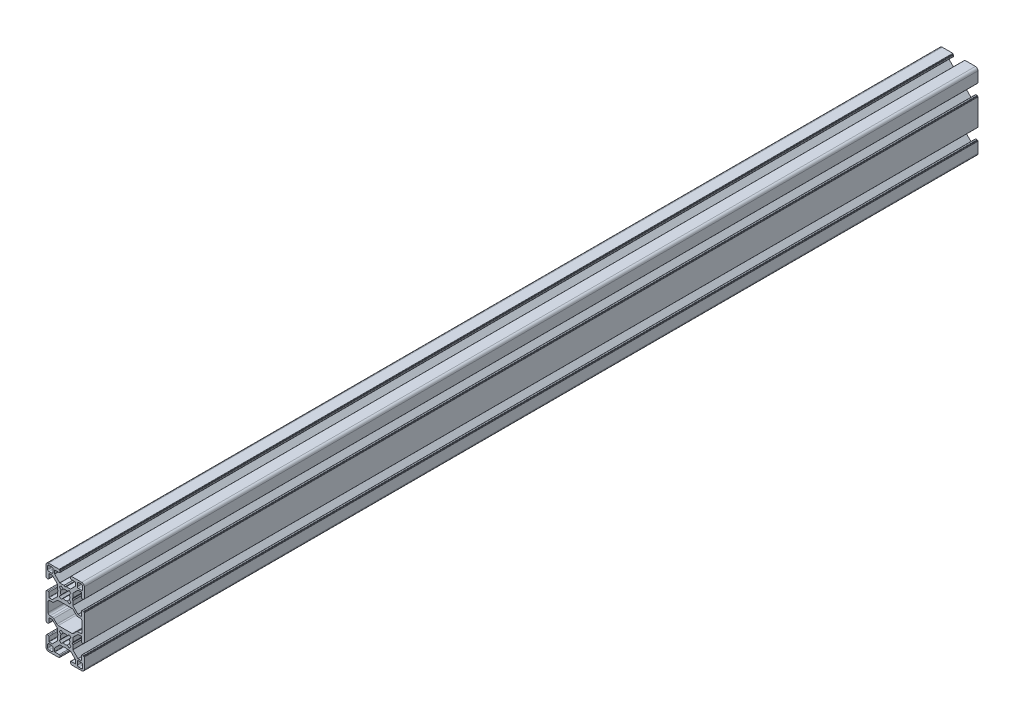
SolidWorks part; units mm, degrees
material "1060 Alloy"
ref_plane "Front" through (0, 0, 0) normal (0, 0, 1) x (1, 0, 0)
ref_plane "Top" through (0, 0, 0) normal (0, 1, 0) x (1, 0, 0)
ref_plane "Right" through (0, 0, 0) normal (1, 0, 0) x (0, 0, -1)
ref_plane "Plane1" through (0, 0, 25) normal (0, 0, 1) x (1, 0, 0)
sketch "Sketch1" plane through (0, 0, 25) normal (0, 0, 1) x (1, 0, 0)
  line L0 (-9.5, 12.7) -> (-9.5, 10.5)
  line L1 (-10.5, 9.5) -> (-12.7, 9.5)
  line L2 (-13.7, 10.5) -> (-13.7, 12.7)
  line L3 (-12.7, 13.7) -> (-10.5, 13.7)
  line L4 (12.7, 9.5) -> (10.5, 9.5)
  line L5 (9.5, 10.5) -> (9.5, 12.7)
  line L6 (10.5, 13.7) -> (12.7, 13.7)
  line L7 (13.7, 12.7) -> (13.7, 10.5)
  line L8 (-12.7, -39.5) -> (-10.5, -39.5)
  line L9 (-9.5, -40.5) -> (-9.5, -42.7)
  line L10 (-10.5, -43.7) -> (-12.7, -43.7)
  line L11 (-13.7, -42.7) -> (-13.7, -40.5)
  line L12 (9.5, -42.7) -> (9.5, -40.5)
  line L13 (10.5, -39.5) -> (12.7, -39.5)
  line L14 (13.7, -40.5) -> (13.7, -42.7)
  line L15 (12.7, -43.7) -> (10.5, -43.7)
  line L16 (-3.2806, 1.6001) -> (-4.5184, 3.1359)
  line L17 (-3.1547, 4.5053) -> (-1.6001, 3.2806)
  line L18 (1.6001, 3.2806) -> (3.1547, 4.5053)
  line L19 (4.5184, 3.1359) -> (3.2806, 1.6001)
  line L20 (3.2806, -1.6001) -> (4.5184, -3.1359)
  line L21 (3.1547, -4.5053) -> (1.6001, -3.2806)
  line L22 (-1.6001, -3.2806) -> (-3.1547, -4.5053)
  line L23 (-4.5184, -3.1359) -> (-3.2806, -1.6001)
  line L24 (-4.5184, -33.1359) -> (-3.2806, -31.6001)
  line L25 (-3.2806, -28.3999) -> (-4.5184, -26.8641)
  line L26 (-3.1547, -25.4947) -> (-1.6001, -26.7194)
  line L27 (1.6001, -26.7194) -> (3.1547, -25.4947)
  line L28 (4.5184, -26.8641) -> (3.2806, -28.3999)
  line L29 (3.2806, -31.6001) -> (4.5184, -33.1359)
  line L30 (3.1547, -34.5053) -> (1.6001, -33.2806)
  line L31 (-1.6001, -33.2806) -> (-3.1547, -34.5053)
  line L32 (8.9272, -20.5393) -> (6.4104, -23.0562)
  line L33 (5.3497, -23.4955) -> (-5.3497, -23.4955)
  line L34 (-6.4104, -23.0562) -> (-8.9272, -20.5393)
  line L35 (-9.9879, -20.1) -> (-11.85, -20.1)
  line L36 (-13.35, -18.6) -> (-13.35, -11.4)
  line L37 (-11.85, -9.9) -> (-9.9879, -9.9)
  line L38 (-8.9272, -9.4607) -> (-6.4104, -6.9438)
  line L39 (-5.3497, -6.5045) -> (5.3497, -6.5045)
  line L40 (6.4104, -6.9438) -> (8.9272, -9.4607)
  line L41 (9.9879, -9.9) -> (11.85, -9.9)
  line L42 (13.35, -11.4) -> (13.35, -18.6)
  line L43 (11.85, -20.1) -> (9.9879, -20.1)
  line L44 (13.4, -25.95) -> (14.3, -25.95)
  line L45 (14.5, -25.75) -> (14.5, -25.65)
  line L46 (14.7, -25.45) -> (14.8, -25.45)
  line L47 (15, -25.25) -> (15, -4.75)
  line L48 (14.8, -4.55) -> (14.7, -4.55)
  line L49 (14.5, -4.35) -> (14.5, -4.25)
  line L50 (14.3, -4.05) -> (13.4, -4.05)
  line L51 (12.8, -4.65) -> (12.8, -8.05)
  line L52 (12.6, -8.25) -> (10.1328, -8.25)
  line L53 (9.9914, -8.1914) -> (6.063, -4.263)
  line L54 (6.0045, -4.1216) -> (6.0045, -0.9)
  line L55 (6.0045, -0.9) -> (5.5426, -0.1)
  line L56 (5.5426, 0.1) -> (6.0045, 0.9)
  line L57 (6.0045, 0.9) -> (6.0045, 4.1216)
  line L58 (6.063, 4.263) -> (9.9914, 8.1914)
  line L59 (10.1328, 8.25) -> (12.6, 8.25)
  line L60 (12.8, 8.05) -> (12.8, 4.65)
  line L61 (13.4, 4.05) -> (14.3, 4.05)
  line L62 (14.5, 4.25) -> (14.5, 4.35)
  line L63 (14.7, 4.55) -> (14.8, 4.55)
  line L64 (15, 4.75) -> (15, 13)
  line L65 (13, 15) -> (4.75, 15)
  line L66 (4.55, 14.8) -> (4.55, 14.7)
  line L67 (4.35, 14.5) -> (4.25, 14.5)
  line L68 (4.05, 14.3) -> (4.05, 13.4)
  line L69 (4.65, 12.8) -> (8.05, 12.8)
  line L70 (8.25, 12.6) -> (8.25, 10.1328)
  line L71 (8.1914, 9.9914) -> (4.2586, 6.0586)
  line L72 (4.1172, 6) -> (0.9, 6)
  line L73 (0.9, 6) -> (0.1019, 5.5392)
  line L74 (-0.1019, 5.5392) -> (-0.9, 6)
  line L75 (-0.9, 6) -> (-4.1172, 6)
  line L76 (-4.2586, 6.0586) -> (-8.1914, 9.9914)
  line L77 (-8.25, 10.1328) -> (-8.25, 12.6)
  line L78 (-8.05, 12.8) -> (-4.65, 12.8)
  line L79 (-4.05, 13.4) -> (-4.05, 14.3)
  line L80 (-4.25, 14.5) -> (-4.35, 14.5)
  line L81 (-4.55, 14.7) -> (-4.55, 14.8)
  line L82 (-4.75, 15) -> (-13, 15)
  line L83 (-15, 13) -> (-15, 4.75)
  line L84 (-14.8, 4.55) -> (-14.7, 4.55)
  line L85 (-14.5, 4.35) -> (-14.5, 4.25)
  line L86 (-14.3, 4.05) -> (-13.4, 4.05)
  line L87 (-12.8, 4.65) -> (-12.8, 8.05)
  line L88 (-12.6, 8.25) -> (-10.1328, 8.25)
  line L89 (-9.9914, 8.1914) -> (-6.063, 4.263)
  line L90 (-6.0045, 4.1216) -> (-6.0045, 0.9)
  line L91 (-6.0045, 0.9) -> (-5.5426, 0.1)
  line L92 (-5.5426, -0.1) -> (-6.0045, -0.9)
  line L93 (-6.0045, -0.9) -> (-6.0045, -4.1216)
  line L94 (-6.063, -4.263) -> (-9.9914, -8.1914)
  line L95 (-10.1328, -8.25) -> (-12.6, -8.25)
  line L96 (-12.8, -8.05) -> (-12.8, -4.65)
  line L97 (-13.4, -4.05) -> (-14.3, -4.05)
  line L98 (-14.5, -4.25) -> (-14.5, -4.35)
  line L99 (-14.7, -4.55) -> (-14.8, -4.55)
  line L100 (-15, -4.75) -> (-15, -25.25)
  line L101 (-14.8, -25.45) -> (-14.7, -25.45)
  line L102 (-14.5, -25.65) -> (-14.5, -25.75)
  line L103 (-14.3, -25.95) -> (-13.4, -25.95)
  line L104 (-12.8, -25.35) -> (-12.8, -21.95)
  line L105 (-12.6, -21.75) -> (-10.1328, -21.75)
  line L106 (-9.9914, -21.8086) -> (-6.063, -25.737)
  line L107 (-6.0045, -25.8784) -> (-6.0045, -29.1)
  line L108 (-6.0045, -29.1) -> (-5.5426, -29.9)
  line L109 (-5.5426, -30.1) -> (-6.0045, -30.9)
  line L110 (-6.0045, -30.9) -> (-6.0045, -34.1216)
  line L111 (-6.063, -34.263) -> (-9.9914, -38.1914)
  line L112 (-10.1328, -38.25) -> (-12.6, -38.25)
  line L113 (-12.8, -38.05) -> (-12.8, -34.65)
  line L114 (-13.4, -34.05) -> (-14.3, -34.05)
  line L115 (-14.5, -34.25) -> (-14.5, -34.35)
  line L116 (-14.7, -34.55) -> (-14.8, -34.55)
  line L117 (-15, -34.75) -> (-15, -43)
  line L118 (-13, -45) -> (-4.75, -45)
  line L119 (-4.55, -44.8) -> (-4.55, -44.7)
  line L120 (-4.35, -44.5) -> (-4.25, -44.5)
  line L121 (-4.05, -44.3) -> (-4.05, -43.4)
  line L122 (-4.65, -42.8) -> (-8.05, -42.8)
  line L123 (-8.25, -42.6) -> (-8.25, -40.1328)
  line L124 (-8.1914, -39.9914) -> (-4.2586, -36.0586)
  line L125 (-4.1172, -36) -> (-0.9, -36)
  line L126 (-0.9, -36) -> (-0.1019, -35.5392)
  line L127 (0.1019, -35.5392) -> (0.9, -36)
  line L128 (0.9, -36) -> (4.1172, -36)
  line L129 (4.2586, -36.0586) -> (8.1914, -39.9914)
  line L130 (8.25, -40.1328) -> (8.25, -42.6)
  line L131 (8.05, -42.8) -> (4.65, -42.8)
  line L132 (4.05, -43.4) -> (4.05, -44.3)
  line L133 (4.25, -44.5) -> (4.35, -44.5)
  line L134 (4.55, -44.7) -> (4.55, -44.8)
  line L135 (4.75, -45) -> (13, -45)
  line L136 (15, -43) -> (15, -34.75)
  line L137 (14.8, -34.55) -> (14.7, -34.55)
  line L138 (14.5, -34.35) -> (14.5, -34.25)
  line L139 (14.3, -34.05) -> (13.4, -34.05)
  line L140 (12.8, -34.65) -> (12.8, -38.05)
  line L141 (12.6, -38.25) -> (10.1328, -38.25)
  line L142 (9.9914, -38.1914) -> (6.063, -34.263)
  line L143 (6.0045, -34.1216) -> (6.0045, -30.9)
  line L144 (6.0045, -30.9) -> (5.5426, -30.1)
  line L145 (5.5426, -29.9) -> (6.0045, -29.1)
  line L146 (6.0045, -29.1) -> (6.0045, -25.8784)
  line L147 (6.063, -25.737) -> (9.9914, -21.8086)
  line L148 (10.1328, -21.75) -> (12.6, -21.75)
  line L149 (12.8, -21.95) -> (12.8, -25.35)
  arc A0 (-9.5, 10.5) -> (-10.5, 9.5) centre (-10.5, 10.5) cw
  arc A1 (-12.7, 9.5) -> (-13.7, 10.5) centre (-12.7, 10.5) cw
  arc A2 (-13.7, 12.7) -> (-12.7, 13.7) centre (-12.7, 12.7) cw
  arc A3 (-10.5, 13.7) -> (-9.5, 12.7) centre (-10.5, 12.7) cw
  arc A4 (10.5, 9.5) -> (9.5, 10.5) centre (10.5, 10.5) cw
  arc A5 (9.5, 12.7) -> (10.5, 13.7) centre (10.5, 12.7) cw
  arc A6 (12.7, 13.7) -> (13.7, 12.7) centre (12.7, 12.7) cw
  arc A7 (13.7, 10.5) -> (12.7, 9.5) centre (12.7, 10.5) cw
  arc A8 (-10.5, -39.5) -> (-9.5, -40.5) centre (-10.5, -40.5) cw
  arc A9 (-9.5, -42.7) -> (-10.5, -43.7) centre (-10.5, -42.7) cw
  arc A10 (-12.7, -43.7) -> (-13.7, -42.7) centre (-12.7, -42.7) cw
  arc A11 (-13.7, -40.5) -> (-12.7, -39.5) centre (-12.7, -40.5) cw
  arc A12 (9.5, -40.5) -> (10.5, -39.5) centre (10.5, -40.5) cw
  arc A13 (12.7, -39.5) -> (13.7, -40.5) centre (12.7, -40.5) cw
  arc A14 (13.7, -42.7) -> (12.7, -43.7) centre (12.7, -42.7) cw
  arc A15 (10.5, -43.7) -> (9.5, -42.7) centre (10.5, -42.7) cw
  arc A16 (-4.5184, 3.1359) -> (-3.1547, 4.5053) centre (0, 0) cw
  arc A17 (-1.6001, 3.2806) -> (1.6001, 3.2806) centre (0, 0) cw
  arc A18 (3.1547, 4.5053) -> (4.5184, 3.1359) centre (0, 0) cw
  arc A19 (3.2806, 1.6001) -> (3.2806, -1.6001) centre (0, 0) cw
  arc A20 (4.5184, -3.1359) -> (3.1547, -4.5053) centre (0, 0) cw
  arc A21 (1.6001, -3.2806) -> (-1.6001, -3.2806) centre (0, 0) cw
  arc A22 (-3.1547, -4.5053) -> (-4.5184, -3.1359) centre (0, 0) cw
  arc A23 (-3.2806, -1.6001) -> (-3.2806, 1.6001) centre (0, 0) cw
  arc A24 (-3.2806, -31.6001) -> (-3.2806, -28.3999) centre (0, -30) cw
  arc A25 (-4.5184, -26.8641) -> (-3.1547, -25.4947) centre (0, -30) cw
  arc A26 (-1.6001, -26.7194) -> (1.6001, -26.7194) centre (0, -30) cw
  arc A27 (3.1547, -25.4947) -> (4.5184, -26.8641) centre (0, -30) cw
  arc A28 (3.2806, -28.3999) -> (3.2806, -31.6001) centre (0, -30) cw
  arc A29 (4.5184, -33.1359) -> (3.1547, -34.5053) centre (0, -30) cw
  arc A30 (1.6001, -33.2806) -> (-1.6001, -33.2806) centre (0, -30) cw
  arc A31 (-3.1547, -34.5053) -> (-4.5184, -33.1359) centre (0, -30) cw
  arc A32 (6.4104, -23.0562) -> (5.3497, -23.4955) centre (5.3497, -21.9955) cw
  arc A33 (-5.3497, -23.4955) -> (-6.4104, -23.0562) centre (-5.3497, -21.9955) cw
  arc A34 (-8.9272, -20.5393) -> (-9.9879, -20.1) centre (-9.9879, -21.6) ccw
  arc A35 (-11.85, -20.1) -> (-13.35, -18.6) centre (-11.85, -18.6) cw
  arc A36 (-13.35, -11.4) -> (-11.85, -9.9) centre (-11.85, -11.4) cw
  arc A37 (-9.9879, -9.9) -> (-8.9272, -9.4607) centre (-9.9879, -8.4) ccw
  arc A38 (-6.4104, -6.9438) -> (-5.3497, -6.5045) centre (-5.3497, -8.0045) cw
  arc A39 (5.3497, -6.5045) -> (6.4104, -6.9438) centre (5.3497, -8.0045) cw
  arc A40 (8.9272, -9.4607) -> (9.9879, -9.9) centre (9.9879, -8.4) ccw
  arc A41 (11.85, -9.9) -> (13.35, -11.4) centre (11.85, -11.4) cw
  arc A42 (13.35, -18.6) -> (11.85, -20.1) centre (11.85, -18.6) cw
  arc A43 (9.9879, -20.1) -> (8.9272, -20.5393) centre (9.9879, -21.6) ccw
  arc A44 (12.8, -25.35) -> (13.4, -25.95) centre (13.4, -25.35) ccw
  arc A45 (14.3, -25.95) -> (14.5, -25.75) centre (14.3, -25.75) ccw
  arc A46 (14.5, -25.65) -> (14.7, -25.45) centre (14.7, -25.65) cw
  arc A47 (14.8, -25.45) -> (15, -25.25) centre (14.8, -25.25) ccw
  arc A48 (15, -4.75) -> (14.8, -4.55) centre (14.8, -4.75) ccw
  arc A49 (14.7, -4.55) -> (14.5, -4.35) centre (14.7, -4.35) cw
  arc A50 (14.5, -4.25) -> (14.3, -4.05) centre (14.3, -4.25) ccw
  arc A51 (13.4, -4.05) -> (12.8, -4.65) centre (13.4, -4.65) ccw
  arc A52 (12.8, -8.05) -> (12.6, -8.25) centre (12.6, -8.05) cw
  arc A53 (10.1328, -8.25) -> (9.9914, -8.1914) centre (10.1328, -8.05) cw
  arc A54 (6.063, -4.263) -> (6.0045, -4.1216) centre (6.2045, -4.1216) cw
  arc A55 (5.5426, -0.1) -> (5.5426, 0.1) centre (5.7158, 0) cw
  arc A56 (6.0045, 4.1216) -> (6.063, 4.263) centre (6.2045, 4.1216) cw
  arc A57 (9.9914, 8.1914) -> (10.1328, 8.25) centre (10.1328, 8.05) cw
  arc A58 (12.6, 8.25) -> (12.8, 8.05) centre (12.6, 8.05) cw
  arc A59 (12.8, 4.65) -> (13.4, 4.05) centre (13.4, 4.65) ccw
  arc A60 (14.3, 4.05) -> (14.5, 4.25) centre (14.3, 4.25) ccw
  arc A61 (14.5, 4.35) -> (14.7, 4.55) centre (14.7, 4.35) cw
  arc A62 (14.8, 4.55) -> (15, 4.75) centre (14.8, 4.75) ccw
  arc A63 (15, 13) -> (13, 15) centre (13, 13) ccw
  arc A64 (4.75, 15) -> (4.55, 14.8) centre (4.75, 14.8) ccw
  arc A65 (4.55, 14.7) -> (4.35, 14.5) centre (4.35, 14.7) cw
  arc A66 (4.25, 14.5) -> (4.05, 14.3) centre (4.25, 14.3) ccw
  arc A67 (4.05, 13.4) -> (4.65, 12.8) centre (4.65, 13.4) ccw
  arc A68 (8.05, 12.8) -> (8.25, 12.6) centre (8.05, 12.6) cw
  arc A69 (8.25, 10.1328) -> (8.1914, 9.9914) centre (8.05, 10.1328) cw
  arc A70 (4.2586, 6.0586) -> (4.1172, 6) centre (4.1172, 6.2) cw
  arc A71 (0.1019, 5.5392) -> (-0.1019, 5.5392) centre (0, 5.7158) cw
  arc A72 (-4.1172, 6) -> (-4.2586, 6.0586) centre (-4.1172, 6.2) cw
  arc A73 (-8.1914, 9.9914) -> (-8.25, 10.1328) centre (-8.05, 10.1328) cw
  arc A74 (-8.25, 12.6) -> (-8.05, 12.8) centre (-8.05, 12.6) cw
  arc A75 (-4.65, 12.8) -> (-4.05, 13.4) centre (-4.65, 13.4) ccw
  arc A76 (-4.05, 14.3) -> (-4.25, 14.5) centre (-4.25, 14.3) ccw
  arc A77 (-4.35, 14.5) -> (-4.55, 14.7) centre (-4.35, 14.7) cw
  arc A78 (-4.55, 14.8) -> (-4.75, 15) centre (-4.75, 14.8) ccw
  arc A79 (-13, 15) -> (-15, 13) centre (-13, 13) ccw
  arc A80 (-15, 4.75) -> (-14.8, 4.55) centre (-14.8, 4.75) ccw
  arc A81 (-14.7, 4.55) -> (-14.5, 4.35) centre (-14.7, 4.35) cw
  arc A82 (-14.5, 4.25) -> (-14.3, 4.05) centre (-14.3, 4.25) ccw
  arc A83 (-13.4, 4.05) -> (-12.8, 4.65) centre (-13.4, 4.65) ccw
  arc A84 (-12.8, 8.05) -> (-12.6, 8.25) centre (-12.6, 8.05) cw
  arc A85 (-10.1328, 8.25) -> (-9.9914, 8.1914) centre (-10.1328, 8.05) cw
  arc A86 (-6.063, 4.263) -> (-6.0045, 4.1216) centre (-6.2045, 4.1216) cw
  arc A87 (-5.5426, 0.1) -> (-5.5426, -0.1) centre (-5.7158, 0) cw
  arc A88 (-6.0045, -4.1216) -> (-6.063, -4.263) centre (-6.2045, -4.1216) cw
  arc A89 (-9.9914, -8.1914) -> (-10.1328, -8.25) centre (-10.1328, -8.05) cw
  arc A90 (-12.6, -8.25) -> (-12.8, -8.05) centre (-12.6, -8.05) cw
  arc A91 (-12.8, -4.65) -> (-13.4, -4.05) centre (-13.4, -4.65) ccw
  arc A92 (-14.3, -4.05) -> (-14.5, -4.25) centre (-14.3, -4.25) ccw
  arc A93 (-14.5, -4.35) -> (-14.7, -4.55) centre (-14.7, -4.35) cw
  arc A94 (-14.8, -4.55) -> (-15, -4.75) centre (-14.8, -4.75) ccw
  arc A95 (-15, -25.25) -> (-14.8, -25.45) centre (-14.8, -25.25) ccw
  arc A96 (-14.7, -25.45) -> (-14.5, -25.65) centre (-14.7, -25.65) cw
  arc A97 (-14.5, -25.75) -> (-14.3, -25.95) centre (-14.3, -25.75) ccw
  arc A98 (-13.4, -25.95) -> (-12.8, -25.35) centre (-13.4, -25.35) ccw
  arc A99 (-12.8, -21.95) -> (-12.6, -21.75) centre (-12.6, -21.95) cw
  arc A100 (-10.1328, -21.75) -> (-9.9914, -21.8086) centre (-10.1328, -21.95) cw
  arc A101 (-6.063, -25.737) -> (-6.0045, -25.8784) centre (-6.2045, -25.8784) cw
  arc A102 (-5.5426, -29.9) -> (-5.5426, -30.1) centre (-5.7158, -30) cw
  arc A103 (-6.0045, -34.1216) -> (-6.063, -34.263) centre (-6.2045, -34.1216) cw
  arc A104 (-9.9914, -38.1914) -> (-10.1328, -38.25) centre (-10.1328, -38.05) cw
  arc A105 (-12.6, -38.25) -> (-12.8, -38.05) centre (-12.6, -38.05) cw
  arc A106 (-12.8, -34.65) -> (-13.4, -34.05) centre (-13.4, -34.65) ccw
  arc A107 (-14.3, -34.05) -> (-14.5, -34.25) centre (-14.3, -34.25) ccw
  arc A108 (-14.5, -34.35) -> (-14.7, -34.55) centre (-14.7, -34.35) cw
  arc A109 (-14.8, -34.55) -> (-15, -34.75) centre (-14.8, -34.75) ccw
  arc A110 (-15, -43) -> (-13, -45) centre (-13, -43) ccw
  arc A111 (-4.75, -45) -> (-4.55, -44.8) centre (-4.75, -44.8) ccw
  arc A112 (-4.55, -44.7) -> (-4.35, -44.5) centre (-4.35, -44.7) cw
  arc A113 (-4.25, -44.5) -> (-4.05, -44.3) centre (-4.25, -44.3) ccw
  arc A114 (-4.05, -43.4) -> (-4.65, -42.8) centre (-4.65, -43.4) ccw
  arc A115 (-8.05, -42.8) -> (-8.25, -42.6) centre (-8.05, -42.6) cw
  arc A116 (-8.25, -40.1328) -> (-8.1914, -39.9914) centre (-8.05, -40.1328) cw
  arc A117 (-4.2586, -36.0586) -> (-4.1172, -36) centre (-4.1172, -36.2) cw
  arc A118 (-0.1019, -35.5392) -> (0.1019, -35.5392) centre (0, -35.7158) cw
  arc A119 (4.1172, -36) -> (4.2586, -36.0586) centre (4.1172, -36.2) cw
  arc A120 (8.1914, -39.9914) -> (8.25, -40.1328) centre (8.05, -40.1328) cw
  arc A121 (8.25, -42.6) -> (8.05, -42.8) centre (8.05, -42.6) cw
  arc A122 (4.65, -42.8) -> (4.05, -43.4) centre (4.65, -43.4) ccw
  arc A123 (4.05, -44.3) -> (4.25, -44.5) centre (4.25, -44.3) ccw
  arc A124 (4.35, -44.5) -> (4.55, -44.7) centre (4.35, -44.7) cw
  arc A125 (4.55, -44.8) -> (4.75, -45) centre (4.75, -44.8) ccw
  arc A126 (13, -45) -> (15, -43) centre (13, -43) ccw
  arc A127 (15, -34.75) -> (14.8, -34.55) centre (14.8, -34.75) ccw
  arc A128 (14.7, -34.55) -> (14.5, -34.35) centre (14.7, -34.35) cw
  arc A129 (14.5, -34.25) -> (14.3, -34.05) centre (14.3, -34.25) ccw
  arc A130 (13.4, -34.05) -> (12.8, -34.65) centre (13.4, -34.65) ccw
  arc A131 (12.8, -38.05) -> (12.6, -38.25) centre (12.6, -38.05) cw
  arc A132 (10.1328, -38.25) -> (9.9914, -38.1914) centre (10.1328, -38.05) cw
  arc A133 (6.063, -34.263) -> (6.0045, -34.1216) centre (6.2045, -34.1216) cw
  arc A134 (5.5426, -30.1) -> (5.5426, -29.9) centre (5.7158, -30) cw
  arc A135 (6.0045, -25.8784) -> (6.063, -25.737) centre (6.2045, -25.8784) cw
  arc A136 (9.9914, -21.8086) -> (10.1328, -21.75) centre (10.1328, -21.95) cw
  arc A137 (12.6, -21.75) -> (12.8, -21.95) centre (12.6, -21.95) cw
extrude "Boss-Extrude1" add sketch "Sketch1" against normal blind 700
sketch "Sketch2" plane through (15, 0, 0) normal (1, 0, 0) x (0, 0, -1)
  line L0 (-25, -30) -> (30, -30) construction
  line L1 (-25, 0.9) -> (-25, 4.1216) construction
  line L2 (-25, 1.6001) -> (-25, -1.6001) construction
  line L3 (675, 15) -> (-25, 15) construction
  line L4 (-25, 4.75) -> (-25, 13) construction
  circle A0 centre (30, -30) radius 3
  dimension "D2" = 6
  dimension "D1" = 45
  dimension "D3" = 55
extrude "Cut-Extrude1" cut sketch "Sketch2" against normal through all
sketch "Sketch3" plane through (0, -45, 0) normal (0, -1, 0) x (1, 0, 0)
  line L0 (0, 25) -> (0, -75) construction
  line L1 (0.1019, 25) -> (-0.1019, 25) construction
  line L2 (0, -675) -> (0, -595) construction
  line L3 (-0.1019, -675) -> (0.1019, -675) construction
  circle A0 centre (0, -75) radius 3
  circle A1 centre (0, -595) radius 3
  dimension "D2" = 6
  dimension "D4" = 6
  dimension "D1" = 100
  dimension "D3" = 80
extrude "Cut-Extrude2" cut sketch "Sketch3" against normal through all
